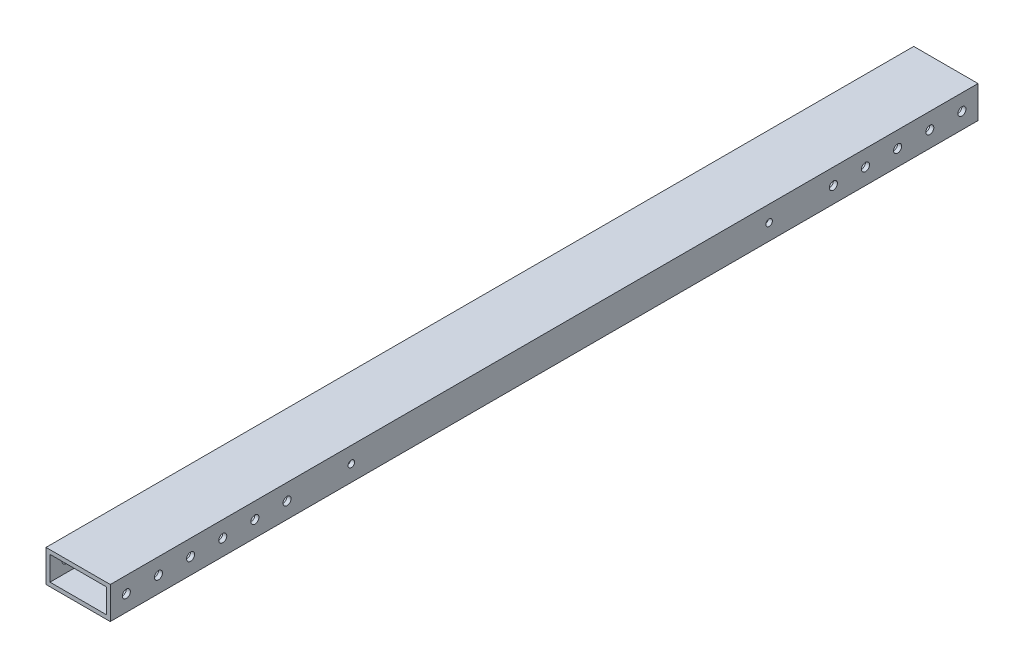
SolidWorks part; units mm, degrees
material "6061 Alloy"
ref_plane "Front Plane" through (0, 0, 0) normal (0, 0, 1) x (1, 0, 0)
ref_plane "Top Plane" through (0, 0, 0) normal (0, 1, 0) x (1, 0, 0)
ref_plane "Right Plane" through (0, 0, 0) normal (1, 0, 0) x (0, 0, -1)
sketch "Sketch1" plane through (0, 0, 0) normal (0, 0, 1) x (1, 0, 0)
  line L0 (-22.225, 9.525) -> (22.225, 9.525)
  line L2 (-25.4, 12.7) -> (25.4, 12.7)
  line L3 (-25.4, 12.7) -> (-25.4, -12.7)
  line L4 (-25.4, -12.7) -> (25.4, -12.7)
  line L5 (25.4, 12.7) -> (25.4, -12.7)
  line L10 (22.225, 9.525) -> (22.225, -9.525)
  line L11 (-22.225, -9.525) -> (22.225, -9.525)
  line L12 (-22.225, 9.525) -> (-22.225, -9.525)
  point P12 (0, 12.7)
  point P14 (25.4, 0)
  dimension "Wall Thickness" = 3.175
  dimension "Outside Width" = 50.8
  dimension "Outside Height" = 25.4
  dimension "Inside Height" = 19.05
  dimension "Inside Width" = 44.45
sketch "Sketch2" plane through (0, 0, 0) normal (1, 0, 0) x (0, 0, -1)
  line L0 (342.9, 0) -> (-342.9, 0)
  point P4 (0, 0)
  point P7 (-342.9, 0)
  point P10 (342.9, 0)
  dimension "Length" = 685.8
sketch "Sketch3" plane through (0, 0, 0) normal (0, 0, 1) x (1, 0, 0)
  line L21 (25.4, 12.7) -> (-25.4, 12.7)
  line L22 (25.4, -12.7) -> (25.4, 12.7)
  line L23 (-25.4, -12.7) -> (25.4, -12.7)
  line L24 (-25.4, 12.7) -> (-25.4, -12.7)
  line L25 (25.4, 12.7) -> (-25.4, 12.7)
  line L26 (25.4, -12.7) -> (25.4, 12.7)
  line L27 (-25.4, -12.7) -> (25.4, -12.7)
  line L28 (-25.4, 12.7) -> (-25.4, -12.7)
  line L29 (22.225, 9.525) -> (-22.225, 9.525)
  line L30 (22.225, -9.525) -> (22.225, 9.525)
  line L31 (-22.225, -9.525) -> (22.225, -9.525)
  line L32 (-22.225, 9.525) -> (-22.225, -9.525)
  line L33 (22.225, 9.525) -> (-22.225, 9.525)
  line L34 (22.225, -9.525) -> (22.225, 9.525)
  line L35 (-22.225, -9.525) -> (22.225, -9.525)
  line L36 (-22.225, 9.525) -> (-22.225, -9.525)
  dimension "D1" = 0
  dimension "D2" = 0
extrude "Boss-Extrude1" add sketch "Sketch3" along normal up to vertex (342.9 mm away) and the other way up to vertex (342.9 mm away) up to point (0, 0, 342.9) other way up to point (0, 0, -342.9)
sketch "Drawing Reference" plane through (0, 0, 0) normal (1, 0, 0) x (0, 0, -1)
  line L0 (-342.9, 0) -> (342.9, 0) construction
  line L1 (0, -12.7) -> (0, 12.7) construction
  line L2 (-342.9, -12.7) -> (342.9, -12.7) construction
  line L5 (-342.9, 12.7) -> (342.9, 12.7) construction
  point P7 (-306.324, 0)
  point P8 (306.324, 0)
  dimension "D1" = 36.576
sketch "Sketch5" plane through (25.4, 0, 0) normal (1, 0, 0) x (0, 0, -1)
  line L0 (-342.9, 0) -> (-279.4, 0)
  line L1 (-342.9, -12.7) -> (-342.9, 12.7) construction
  line L2 (-279.4, 0) -> (-254, 0)
  line L3 (-254, 0) -> (-228.6, 0)
  line L4 (-228.6, 0) -> (-203.2, 0)
sketch "Sketch8" plane through (25.4, 0, 0) normal (1, 0, 0) x (0, 0, -1)
  line L0 (342.9, 0) -> (304.8, 0)
  line L1 (342.9, -12.7) -> (342.9, 12.7) construction
  line L2 (304.8, 0) -> (279.4, 0)
  line L3 (279.4, 0) -> (254, 0)
  line L4 (254, 0) -> (228.6, 0)
  line L5 (342.9, 0) -> (330.2, 0)
hole_wizard "1/4 (0.25) Diameter Hole3" positions "Sketch12" profile "Sketch13" hole size "1/4" standard "ANSI Inch" end condition through all
sketch "Sketch12" plane through (-25.4, 0, 0) normal (-1, 0, 0) x (0, 0, 1)
  point P4 (-330.2, 0)
sketch "Sketch13" plane through (-25.4, 0, -330.2) normal (0, 1, 0) x (0, 0, 1)
  line L0 (0, 0) -> (0, 50.8)
  line L1 (0, 50.8) -> (3.175, 50.8)
  line L2 (3.175, 50.8) -> (3.175, 0)
  line L5 (3.175, 0) -> (0, 0)
  line L11 (0, -6.35) -> (0, 107.95) construction
  dimension "Thru Hole Dia." = 6.35
  dimension "Thru Hole Depth" = 50.8
hole_wizard "1/4 (0.25) Diameter Hole4" positions "Sketch14" profile "Sketch15" hole size "1/4" standard "ANSI Inch" end condition through all
sketch "Sketch14" plane through (-25.4, 0, 0) normal (-1, 0, 0) x (0, 0, 1)
  point P0 (304.8, 0)
  point P3 (330.2, 0)
sketch "Sketch15" plane through (-25.4, 0, 304.8) normal (0, 1, 0) x (0, 0, 1)
  line L0 (0, 0) -> (0, 50.8)
  line L1 (0, 50.8) -> (3.175, 50.8)
  line L2 (3.175, 50.8) -> (3.175, 0)
  line L5 (3.175, 0) -> (0, 0)
  line L11 (0, -6.35) -> (0, 107.95) construction
  dimension "Thru Hole Dia." = 6.35
  dimension "Thru Hole Depth" = 50.8
hole_wizard "1/4 (0.25) Diameter Hole5" positions "Sketch17" profile "Sketch18" hole size "1/4" standard "ANSI Inch" end condition through all
sketch "Sketch17" plane through (25.4, 0, 0) normal (1, 0, 0) x (0, 0, -1)
  point P0 (304.8, 0)
  point P3 (279.4, 0)
sketch "Sketch18" plane through (25.4, 0, -304.8) normal (0, 1, 0) x (0, 0, -1)
  line L0 (0, 0) -> (0, 50.8)
  line L1 (0, 50.8) -> (3.175, 50.8)
  line L2 (3.175, 50.8) -> (3.175, 0)
  line L5 (3.175, 0) -> (0, 0)
  line L11 (0, -6.35) -> (0, 107.95) construction
  dimension "Thru Hole Dia." = 6.35
  dimension "Thru Hole Depth" = 50.8
hole_wizard "1/4 (0.25) Diameter Hole6" positions "Sketch19" profile "Sketch20" hole size "1/4" standard "ANSI Inch" end condition through all
sketch "Sketch19" plane through (25.4, 0, 0) normal (1, 0, 0) x (0, 0, -1)
  point P0 (228.6, 0)
  point P3 (254, 0)
sketch "Sketch20" plane through (25.4, 0, -228.6) normal (0, 1, 0) x (0, 0, -1)
  line L0 (0, 0) -> (0, 50.8)
  line L1 (0, 50.8) -> (3.175, 50.8)
  line L2 (3.175, 50.8) -> (3.175, 0)
  line L5 (3.175, 0) -> (0, 0)
  line L11 (0, -6.35) -> (0, 107.95) construction
  dimension "Thru Hole Dia." = 6.35
  dimension "Thru Hole Depth" = 50.8
hole_wizard "1/4 (0.25) Diameter Hole7" positions "Sketch21" profile "Sketch22" hole size "1/4" standard "ANSI Inch" end condition through all
sketch "Sketch21" plane through (25.4, 0, 0) normal (1, 0, 0) x (0, 0, -1)
  point P0 (-203.2, 0)
  point P3 (-228.6, 0)
sketch "Sketch22" plane through (25.4, 0, 203.2) normal (0, 1, 0) x (0, 0, -1)
  line L0 (0, 0) -> (0, 50.8)
  line L1 (0, 50.8) -> (3.175, 50.8)
  line L2 (3.175, 50.8) -> (3.175, 0)
  line L5 (3.175, 0) -> (0, 0)
  line L11 (0, -6.35) -> (0, 107.95) construction
  dimension "Thru Hole Dia." = 6.35
  dimension "Thru Hole Depth" = 50.8
hole_wizard "1/4 (0.25) Diameter Hole8" positions "Sketch23" profile "Sketch24" hole size "1/4" standard "ANSI Inch" end condition through all
sketch "Sketch23" plane through (25.4, 0, 0) normal (1, 0, 0) x (0, 0, -1)
  point P0 (-279.4, 0)
  point P3 (-254, 0)
sketch "Sketch24" plane through (25.4, 0, 279.4) normal (0, 1, 0) x (0, 0, -1)
  line L0 (0, 0) -> (0, 50.8)
  line L1 (0, 50.8) -> (3.175, 50.8)
  line L2 (3.175, 50.8) -> (3.175, 0)
  line L5 (3.175, 0) -> (0, 0)
  line L11 (0, -6.35) -> (0, 107.95) construction
  dimension "Thru Hole Dia." = 6.35
  dimension "Thru Hole Depth" = 50.8
sketch "Sketch25" plane through (25.4, 0, 0) normal (1, 0, 0) x (0, 0, -1)
  line L0 (-203.2, 0) -> (-152.4, 0)
  line L1 (228.6, 0) -> (177.8, 0)
hole_wizard "13/64 (0.20313) Diameter Hole1" positions "Sketch26" profile "Sketch27" hole size "13/64" standard "ANSI Inch" end condition through all
sketch "Sketch26" plane through (25.4, 0, 0) normal (1, 0, 0) x (0, 0, -1)
  point P0 (-152.4, 0)
  point P3 (177.8, 0)
sketch "Sketch27" plane through (25.4, 0, 152.4) normal (0, 1, 0) x (0, 0, -1)
  line L0 (0, 0) -> (0, 50.8)
  line L1 (0, 50.8) -> (2.5798, 50.8)
  line L2 (2.5798, 50.8) -> (2.5798, 0)
  line L5 (2.5798, 0) -> (0, 0)
  line L11 (0, -6.35) -> (0, 107.95) construction
  dimension "Thru Hole Dia." = 5.1595
  dimension "Thru Hole Depth" = 50.8
sketch "Sketch30" plane through (-25.4, 0, 0) normal (-1, 0, 0) x (0, 0, 1)
  point P0 (-128.5875, 0)
  point P1 (-103.1875, 0)
  point P2 (77.7875, 0)
  point P3 (103.1875, 0)
  point P4 (-128.5875, 0)
  point P5 (-103.1875, 0)
  point P6 (77.7875, 0)
  point P7 (103.1875, 0)
hole_wizard "1/2 (0.5) Diameter Hole1" positions "Sketch33" profile "Sketch34" hole size "1/2" standard "ANSI Inch"
sketch "Sketch33" plane through (-25.4, 0, 0) normal (-1, 0, 0) x (0, 0, 1)
  point P0 (-128.5875, 0)
  point P3 (-103.1875, 0)
  point P7 (77.7875, 0)
  point P10 (103.1875, 0)
sketch "Sketch34" plane through (-25.4, 0, -128.5875) normal (0, 1, 0) x (0, 0, 1)
  line L0 (0, 0) -> (0, 10.1655)
  line L1 (0, 10.1655) -> (6.35, 6.35)
  line L2 (6.35, 6.35) -> (6.35, 0)
  line L5 (6.35, 0) -> (0, 0)
  line L10 (0, 10.1655) -> (-6.35, 6.35) construction
  line L11 (0, -6.35) -> (0, 107.95) construction
  dimension "Hole Dia." = 12.7
  dimension "Hole Depth" = 6.35
  dimension "Drill Angle" = 118
equation "\"D1@Drawing Reference\"=\"Outside Width@Sketch1\" * 0.72"
